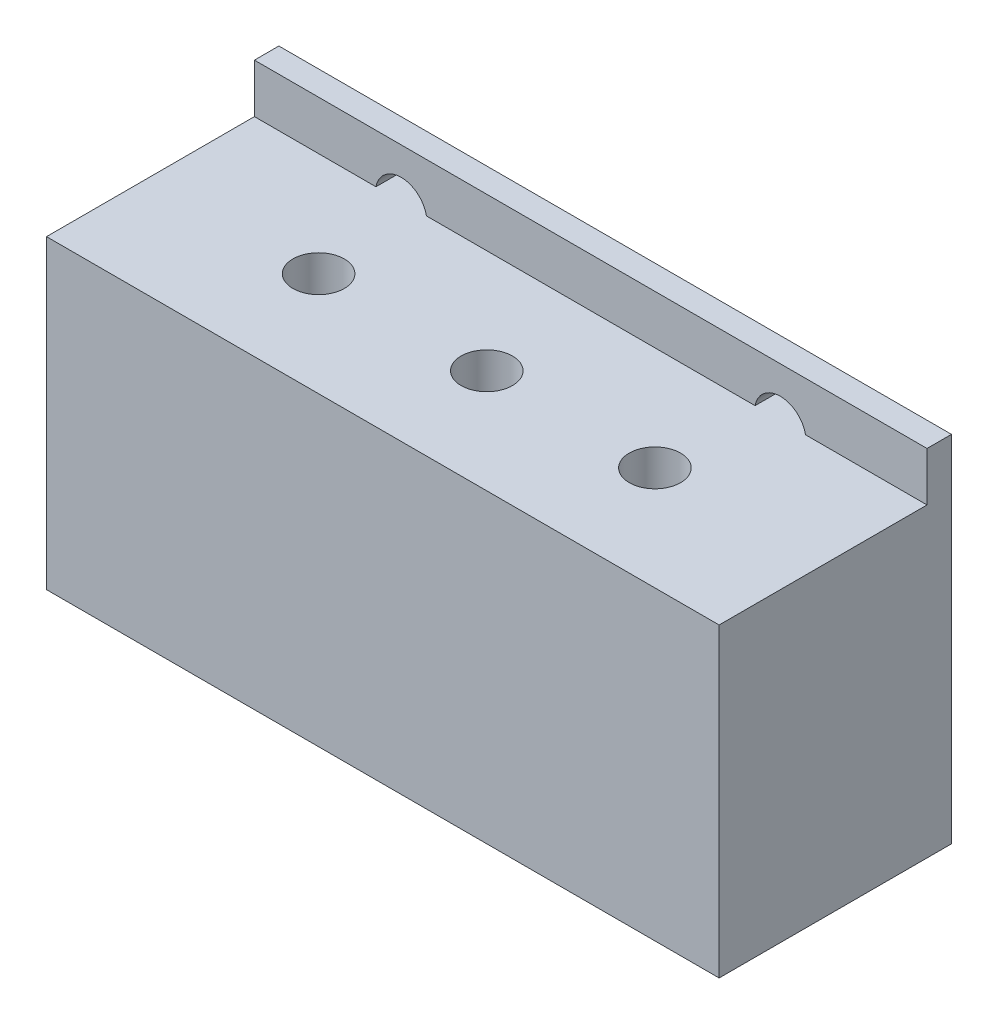
SolidWorks part; units mm, degrees
ref_plane "Front" through (0, 0, 0) normal (0, 0, 1) x (1, 0, 0)
ref_plane "Top" through (0, 0, 0) normal (0, 1, 0) x (1, 0, 0)
ref_plane "Right" through (0, 0, 0) normal (1, 0, 0) x (0, 0, -1)
sketch "Esquisse1" plane through (0, 0, 0) normal (0, 0, 1) x (1, 0, 0)
  line L0 (137.5, 145) -> (137.5, 0) construction
  line L1 (0, 0) -> (275, 0)
  line L2 (0, 0) -> (0, 145)
  line L3 (0, 145) -> (275, 145)
  line L4 (275, 0) -> (275, 145)
  circle A0 centre (60, 123) radius 10.5
  circle A1 centre (25, 85) radius 8
  circle A2 centre (250, 85) radius 8
  circle A3 centre (215, 123) radius 10.5
  dimension "D3" = 21
  dimension "D4" = 16
  dimension "D1" = 145
  dimension "D2" = 275
  dimension "D5" = 25
  dimension "D6" = 60
  dimension "D7" = 60
  dimension "D8" = 22
  dimension "D9" = 137.5
extrude "Boss.-Extru.1" add sketch "Esquisse1" along normal blind 10
sketch "Esquisse2" plane through (0, 0, 0) normal (0, 1, 0) x (1, 0, 0)
  line L1 (275, 0) -> (0, 0)
  line L2 (275, 0) -> (275, -95)
  line L3 (275, -95) -> (0, -95)
  line L4 (0, 0) -> (0, -95)
  dimension "D1" = 95
extrude "Boss.-Extru.2" add sketch "Esquisse2" along normal blind 125
ref_plane "Plan2" through (0, 125, 0) normal (0, 1, 0) x (1, 0, 0)
sketch "Esquisse4" plane through (0, 125, 0) normal (0, 1, 0) x (1, 0, 0)
  line L0 (275, -95) -> (275, -10) construction
  line L1 (0, -95) -> (275, -95) construction
  circle A0 centre (206.25, -52.5) radius 10.5
  circle A1 centre (137.5, -52.5) radius 10.5
  circle A2 centre (68.75, -52.5) radius 10.5
  dimension "D1" = 21
  dimension "D2" = 68.75
  dimension "D4" = 42.5
  dimension "D3" = 3
extrude "Enlèv. mat.-Extru.1" cut sketch "Esquisse4" against normal through all
